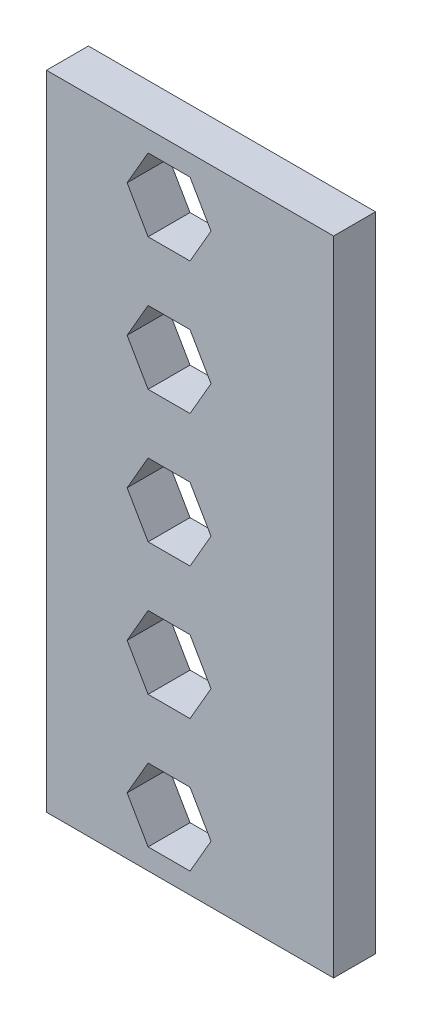
SolidWorks part; units mm, degrees
ref_plane "Front Plane" through (0, 0, 0) normal (0, 0, 1) x (1, 0, 0)
ref_plane "Top Plane" through (0, 0, 0) normal (0, 1, 0) x (1, 0, 0)
ref_plane "Right Plane" through (0, 0, 0) normal (1, 0, 0) x (0, 0, -1)
sketch "Sketch1" plane through (0, 0, 0) normal (0, 0, 1) x (1, 0, 0)
  line L1 (15.6312, -27.5) -> (-15.6312, -27.5)
  line L2 (15.6312, -27.5) -> (15.6312, 27.5)
  line L3 (15.6312, 27.5) -> (-15.6312, 27.5)
  line L4 (-15.6312, -27.5) -> (-15.6312, 27.5)
  line L5 (15.6312, -27.5) -> (-15.6312, 27.5) construction
  line L6 (15.6312, 27.5) -> (-15.6312, -27.5) construction
  point P0 (0, 0)
  dimension "D1" = 31.2625
  dimension "D2" = 55
extrude "Boss-Extrude1" add sketch "Sketch1" along normal blind 3.175
sketch "Sketch2" plane through (0, 0, 3.175) normal (0, 0, 1) x (1, 0, 0)
  line L0 (-15.6312, 27.5) -> (-15.6312, -27.5) construction
  circle A0 centre (0, 0) radius 1.5
  dimension "D1" = 3
extrude "Cut-Extrude1" cut sketch "Sketch2" against normal blind 10
pattern_linear "LPattern1" count 3 spacing 10 along (0, 1, 0) count 3 spacing 10 along (0, -1, 0) of "Cut-Extrude1"
sketch "Sketch3" plane through (0, 0, 3.175) normal (0, 0, 1) x (1, 0, 0)
  line L0 (15.6312, -27.5) -> (15.6312, 27.5) construction
  line L1 (12.4563, -1.5875) -> (18.8062, -1.5875)
  line L2 (12.4563, -1.5875) -> (12.4563, -4.7625)
  line L3 (12.4563, -4.7625) -> (18.8062, -4.7625)
  line L4 (18.8062, -1.5875) -> (18.8062, -4.7625)
  line L5 (12.4563, -1.5875) -> (18.8062, -4.7625) construction
  line L6 (12.4563, -4.7625) -> (18.8062, -1.5875) construction
  point P0 (15.6312, -3.175)
  dimension "D1" = 3.175
  dimension "D2" = 6.35
  dimension "D3" = 3.175
extrude "Cut-Extrude2" cut sketch "Sketch3" against normal blind 10
pattern_linear "LPattern2" count 5 spacing 6.35 along (0, 1, 0) count 5 spacing 6.35 along (0, -1, 0) of "Cut-Extrude2"
sketch "Sketch4" plane through (0, 0, 3.175) normal (0, 0, 1) x (1, 0, 0)
  line L1 (12.4563, 23.8125) -> (15.6312, 23.8125)
  line L2 (12.4563, 23.8125) -> (12.4563, 27.5)
  line L3 (12.4563, 27.5) -> (15.6312, 27.5)
  line L4 (15.6312, 23.8125) -> (15.6312, 27.5)
  line L5 (12.4563, -23.8125) -> (15.6312, -23.8125)
  line L6 (12.4563, -23.8125) -> (12.4563, -26.9875)
  line L7 (12.4563, -26.9875) -> (15.6312, -26.9875)
  line L8 (15.6312, -23.8125) -> (15.6312, -26.9875)
extrude "Cut-Extrude3" cut sketch "Sketch4" against normal blind 10
sketch "Sketch5" plane through (0, 0, 3.175) normal (0, 0, 1) x (1, 0, 0)
  line L0 (-15.6312, -27.5) -> (12.4563, -27.5) construction
  line L1 (-15.6312, 27.5) -> (-9.2812, 27.5)
  line L2 (-15.6312, 27.5) -> (-15.6312, -27.5)
  line L3 (-15.6312, -27.5) -> (-9.2812, -27.5)
  line L4 (-9.2812, 27.5) -> (-9.2812, -27.5)
  dimension "D1" = 6.35
extrude "Cut-Extrude4" cut sketch "Sketch5" against normal blind 10
sketch "Sketch6" plane through (0, 0, 3.175) normal (0, 0, 1) x (1, 0, 0)
  line L0 (12.4563, 27.5) -> (-9.2812, 27.5) construction
  line L1 (-6.1062, 27.5) -> (-2.9312, 27.5)
  line L2 (-6.1062, 27.5) -> (-6.1062, 24.325)
  line L3 (-6.1062, 24.325) -> (-2.9312, 24.325)
  line L4 (-2.9312, 27.5) -> (-2.9312, 24.325)
  line L5 (-9.2812, -27.5) -> (-9.2812, 27.5) construction
  dimension "D1" = 3.175
  dimension "D2" = 3.175
  dimension "D3" = 3.175
extrude "Cut-Extrude5" cut sketch "Sketch6" against normal blind 10
pattern_linear "LPattern3" count 2 spacing 6.35 along (1, 0, 0) count 2 spacing 6.35 of "Cut-Extrude5"
sketch "Sketch7" plane through (0, 0, 3.175) normal (0, 0, 1) x (1, 0, 0)
  line L0 (12.4563, 27.5) -> (12.4563, 20.6375) construction
  line L1 (6.5938, 27.5) -> (12.4563, 27.5)
  line L3 (6.5938, 24.325) -> (12.4563, 24.325)
  line L4 (12.4563, 27.5) -> (12.4563, 24.325)
  line L5 (6.5938, 27.5) -> (6.5938, 24.325)
extrude "Cut-Extrude6" cut sketch "Sketch7" against normal blind 10
mirror "Mirror1" about plane through (0, 0, 0) normal (0, 1, 0) of "LPattern3", "Cut-Extrude6", "Cut-Extrude5"
sketch "Sketch8" plane through (0, 0, 3.175) normal (0, 0, 1) x (1, 0, 0)
  line L0 (-9.2812, -27.5) -> (-9.2812, 27.5) construction
  line L1 (12.4563, 24.325) -> (-9.2812, 24.325)
  line L2 (12.4563, 24.325) -> (12.4563, 27.5)
  line L3 (12.4563, 27.5) -> (-9.2812, 27.5)
  line L4 (-9.2812, 24.325) -> (-9.2812, 27.5)
  line L5 (15.6312, 20.6375) -> (12.4563, 20.6375)
  line L6 (15.6312, 20.6375) -> (15.6312, -20.6375)
  line L7 (15.6312, -20.6375) -> (12.4563, -20.6375)
  line L8 (12.4563, 20.6375) -> (12.4563, -20.6375)
  line L9 (6.5938, -27.5) -> (-9.2812, -27.5)
  line L10 (6.5938, -27.5) -> (6.5938, -24.325)
  line L11 (6.5938, -24.325) -> (-9.2812, -24.325)
  line L12 (-9.2812, -27.5) -> (-9.2812, -24.325)
extrude "Cut-Extrude7" cut sketch "Sketch8" against normal blind 10
sketch "Sketch9" plane through (0, 0, 3.175) normal (0, 0, 1) x (1, 0, 0)
  line L1 (3.1754, 20) -> (1.5877, 22.75)
  line L2 (1.5877, 22.75) -> (-1.5877, 22.75)
  line L3 (-1.5877, 22.75) -> (-3.1754, 20)
  line L4 (-3.1754, 20) -> (-1.5877, 17.25)
  line L5 (-1.5877, 17.25) -> (1.5877, 17.25)
  line L6 (1.5877, 17.25) -> (3.1754, 20)
  circle A0 centre (0, 20) radius 2.75 construction
  dimension "D1" = 5.5
extrude "Cut-Extrude8" cut sketch "Sketch9" against normal blind 10
pattern_linear "LPattern4" count 5 spacing 10 along (0, -1, 0) of "Cut-Extrude8"
